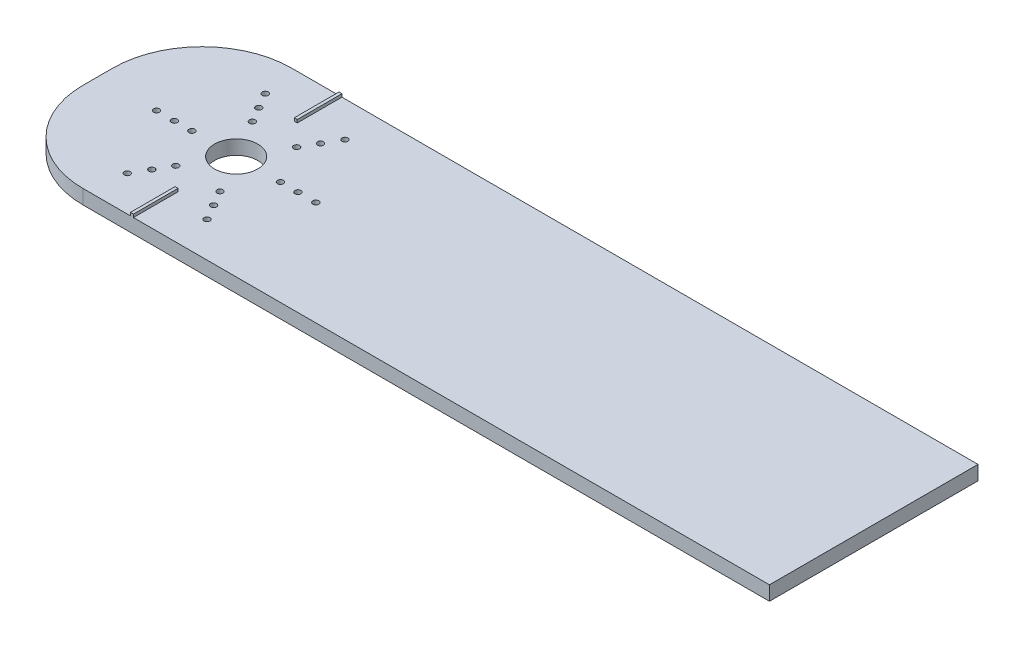
SolidWorks part; units mm, degrees
ref_plane "Front Plane" through (0, 0, 0) normal (0, 0, 1) x (1, 0, 0)
ref_plane "Top Plane" through (0, 0, 0) normal (0, 1, 0) x (1, 0, 0)
ref_plane "Right Plane" through (0, 0, 0) normal (1, 0, 0) x (0, 0, -1)
sketch "Sketch1" plane through (0, 0, 0) normal (0, 1, 0) x (1, 0, 0)
  line L1 (-2.6771, 38.9958) -> (127.5229, 38.9958)
  line L2 (-2.6771, 38.9958) -> (-2.6771, 3.9958)
  line L3 (-2.6771, 3.9958) -> (127.5229, 3.9958)
  line L4 (127.5229, 38.9958) -> (127.5229, 3.9958)
  dimension "D1" = 130.2
  dimension "D2" = 35
extrude "Boss-Extrude1" add sketch "Sketch1" along normal blind 2.4
sketch "Sketch2" plane through (0, 2.4, 0) normal (0, 1, 0) x (1, 0, 0)
  line L0 (20.5229, 38.9958) -> (20.5229, 2.4158) construction
  line L1 (127.5229, 38.9958) -> (-2.6771, 38.9958) construction
  line L2 (-2.6771, 21.4958) -> (127.5229, 21.4958) construction
  line L3 (-2.6771, 38.9958) -> (-2.6771, 3.9958) construction
  line L4 (127.5229, 3.9958) -> (127.5229, 38.9958) construction
  circle A0 centre (16.8079, 27.9303) radius 0.5
  circle A1 centre (15.3404, 30.4721) radius 0.5
  circle A2 centre (13.8379, 33.0745) radius 0.5
  circle A3 centre (24.2379, 27.9303) radius 0.5
  circle A4 centre (20.5229, 21.4958) radius 3.625
  circle A5 centre (13.0929, 21.4958) radius 0.5
  circle A6 centre (10.1579, 21.4958) radius 0.5
  circle A7 centre (7.1529, 21.4958) radius 0.5
  circle A8 centre (25.7054, 30.4721) radius 0.5
  circle A9 centre (27.2079, 33.0745) radius 0.5
  circle A10 centre (27.9529, 21.4958) radius 0.5
  circle A11 centre (30.8879, 21.4958) radius 0.5
  circle A12 centre (33.8929, 21.4958) radius 0.5
  circle A13 centre (24.2379, 15.0612) radius 0.5
  circle A14 centre (25.7054, 12.5194) radius 0.5
  circle A15 centre (27.2079, 9.917) radius 0.5
  circle A16 centre (16.8079, 15.0612) radius 0.5
  circle A17 centre (15.3404, 12.5194) radius 0.5
  circle A18 centre (13.8379, 9.917) radius 0.5
  point P24 (20.5229, 21.4958)
  point P52 (20.5229, 21.4958)
  dimension "D11" = 7.25
  dimension "D12" = 7.43
  dimension "D13" = 10.365
  dimension "D14" = 13.37
  dimension "D15" = 1
  dimension "D16" = 1
  dimension "D17" = 1
  dimension "D1" = 23.2
  dimension "D2" = 6
extrude "Cut-Extrude1" cut sketch "Sketch2" against normal blind 2.4
sketch "Sketch6" plane through (0, 2.4, 0) normal (0, 1, 0) x (1, 0, 0)
  line L0 (-2.6771, 21.4958) -> (127.5229, 21.4958) construction
  line L1 (-2.6771, 38.9958) -> (-2.6771, 3.9958) construction
  line L2 (127.5229, 3.9958) -> (127.5229, 38.9958) construction
  line L3 (20.5229, 21.4958) -> (20.5229, 38.9958) construction
  line L4 (127.5229, 38.9958) -> (-2.6771, 38.9958) construction
  line L5 (20.7729, 3.9958) -> (20.7729, 11.4958)
  line L6 (20.2729, 38.9958) -> (20.7729, 38.9958)
  line L7 (20.2729, 38.9958) -> (20.2729, 31.4958)
  line L8 (20.2729, 31.4958) -> (20.7729, 31.4958)
  line L9 (20.7729, 38.9958) -> (20.7729, 31.4958)
  line L10 (20.2729, 11.4958) -> (20.7729, 11.4958)
  line L11 (20.2729, 3.9958) -> (20.2729, 11.4958)
  line L12 (20.2729, 3.9958) -> (20.7729, 3.9958)
  dimension "D1" = 0.25
  dimension "D2" = 0.5
  dimension "D3" = 7.5
extrude "Boss-Extrude3" add sketch "Sketch6" along normal blind 0.5
fillet "Fillet3" radius 15 2 edges at (-2.6771, 1.2, -3.9958) (-2.6771, 1.2, -38.9958)
